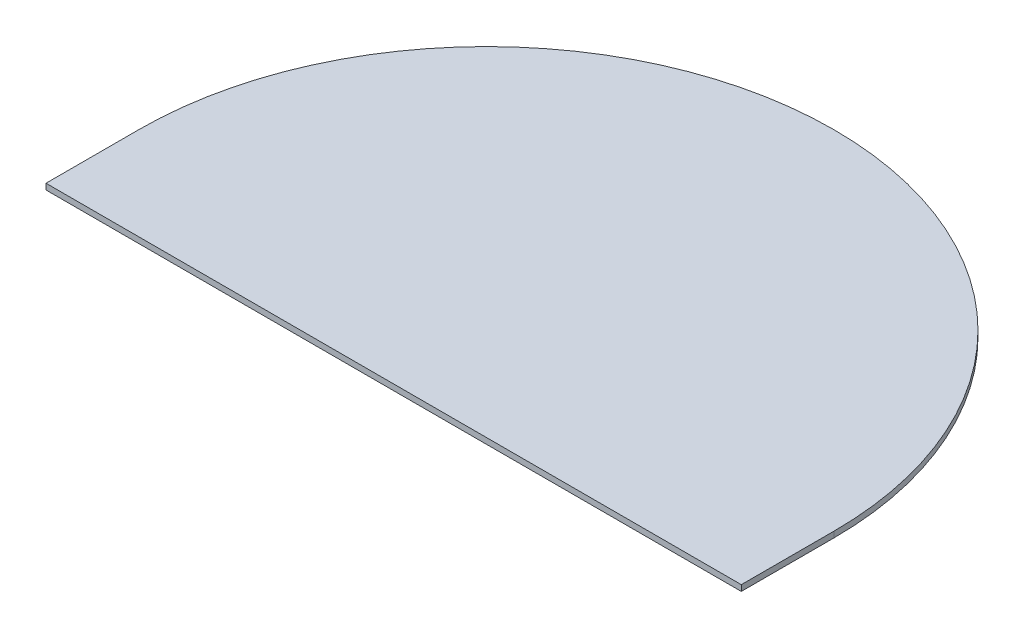
SolidWorks part; units mm, degrees
ref_plane "Plan de face" through (0, 0, 0) normal (0, 0, 1) x (1, 0, 0)
ref_plane "Plan de dessus" through (0, 0, 0) normal (0, 1, 0) x (1, 0, 0)
ref_plane "Plan de droite" through (0, 0, 0) normal (1, 0, 0) x (0, 0, -1)
sketch "Esquisse1" plane through (0, 0, 0) normal (0, 1, 0) x (1, 0, 0)
  line L6 (-375, -75) -> (-75, -75)
  line L7 (-375, -75) -> (-375, 25)
  line L8 (-375, 25) -> (-75, 25)
  line L9 (-75, -75) -> (-75, 25)
  line L10 (-375, -75) -> (-75, 25) construction
  line L11 (-375, 25) -> (-75, -75) construction
  line L12 (-75, -75) -> (75, -75)
  line L13 (-75, -75) -> (-75, 75)
  line L14 (-75, 75) -> (75, 75)
  line L15 (75, -75) -> (75, 75)
  line L16 (-75, -75) -> (75, 75) construction
  line L17 (-75, 75) -> (75, -75) construction
  line L18 (75, -75) -> (375, -75)
  line L19 (75, -75) -> (75, 25)
  line L20 (75, 25) -> (375, 25)
  line L21 (375, -75) -> (375, 25)
  line L22 (75, -75) -> (375, 25) construction
  line L23 (75, 25) -> (375, -75) construction
  arc A0 (-375, 25) -> (375, 25) centre (0, 25) cw
  point P0 (-225, -25)
  point P6 (0, 0)
  point P12 (225, -25)
  dimension "D1" = 150
  dimension "D2" = 300
  dimension "D3" = 150
  dimension "D4" = 100
sketch "Esquisse2" plane through (0, 0, 0) normal (0, 1, 0) x (1, 0, 0)
  line L0 (-375, -75) -> (375, -75)
  line L1 (375, -75) -> (375, 25)
  line L2 (-375, -75) -> (-375, 25)
  arc A0 (-375, 25) -> (375, 25) centre (0, 25) cw
extrude "Boss.-Extru.3" add sketch "Esquisse2" along normal blind 6.35
equation "\"largeur_base_robot\"=150"
equation "\"D1@Esquisse1\"=\"largeur_base_robot\""
equation "\"largeur_base_support_drink\"=318.461"
equation "\"hauteur_base_robot\"=150"
equation "\"D3@Esquisse1\"=\"hauteur_base_robot\""
equation "\"hauteur_base_support_drink\"=100"
equation "\"D4@Esquisse1\"=\"hauteur_base_support_drink\""
